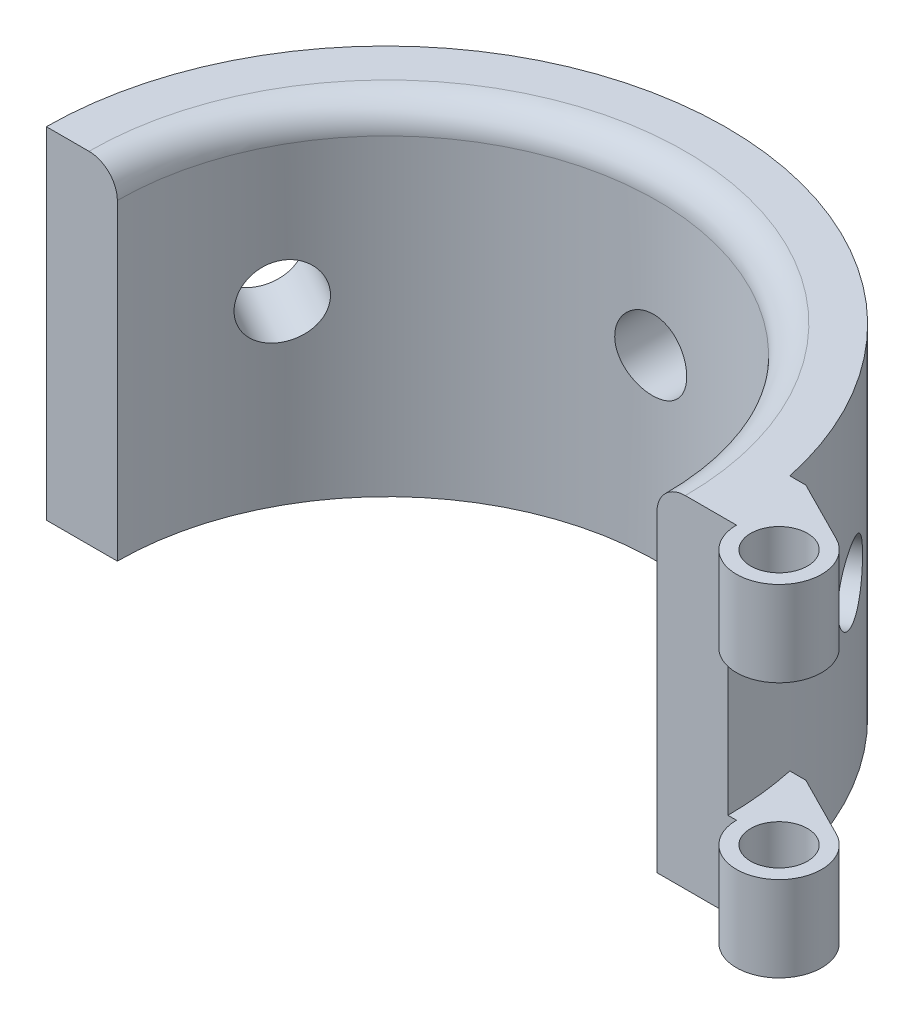
SolidWorks part; units mm, degrees
ref_plane "Front Plane" through (0, 0, 0) normal (0, 0, 1) x (1, 0, 0)
ref_plane "Top Plane" through (0, 0, 0) normal (0, 1, 0) x (1, 0, 0)
ref_plane "Right Plane" through (0, 0, 0) normal (1, 0, 0) x (0, 0, -1)
sketch "Sketch1" plane through (0, 0, 0) normal (0, 1, 0) x (1, 0, 0)
  line L1 (-78.9587, 0) -> (-17.9987, 0)
  arc A0 (-78.9587, 0) -> (-17.9987, 0) centre (-48.4787, -0.1303) cw
  dimension "D1" = 60.96
extrude "Boss-Extrude1" add sketch "Sketch1" along normal blind 30.48 contours L1 A0
ref_plane "Plane1" through (-17.9987, 30.48, 0) normal (1, 0, 0) x (0, 0, -1)
sketch "Sketch3" plane through (0, 0, 0) normal (0, 1, 0) x (1, 0, 0)
  line L0 (-78.9587, 0) -> (-17.9987, 0) construction
  circle A0 centre (-48.4787, 0) radius 24.13
  dimension "D1" = 48.26
extrude "Cut-Extrude4" cut sketch "Sketch3" along normal through all contours A0
sketch "Sketch4" plane through (0, 0, 0) normal (0, 0, 1) x (1, 0, 0)
  circle A0 centre (-48.8244, 15.7989) radius 3.175
  dimension "D1" = 6.35
extrude "Cut-Extrude5" cut sketch "Sketch4" against normal blind 63.754 contours A0
pattern_circular "CirPattern3" count 6 every 60 about axis through (-48.4787, 30.48, 0.1303) along (0, -1, 0) of "Cut-Extrude5"
sketch "Sketch5" plane through (0, 30.48, 0) normal (0, 1, 0) x (1, 0, 0)
  line L0 (-17.2367, 0) -> (-13.4267, 0)
  line L1 (-17.9987, 0) -> (-17.2367, 0)
  line L3 (-18.2527, 6.2015) -> (-17.2367, 6.2015)
  line L5 (-17.2367, 6.2015) -> (-11.7048, 3.3987)
  line L6 (-18.2527, 6.2015) -> (-18.6634, 6.2015)
  arc A0 (-17.2367, 0) -> (-11.7048, 3.3987) centre (-13.4267, 0) ccw
  circle A1 centre (-13.4267, 0) radius 2.54
  arc A2 (-17.9987, 0) -> (-78.9587, 0) centre (-48.4787, -0.1303) ccw construction
  dimension "D2" = 7.62
  dimension "D3" = 5.08
  dimension "D1" = 0.762
extrude "Boss-Extrude2" add sketch "Sketch5" against normal blind 7.62
pattern_linear "LPattern1" count 2 spacing 22.86 along (0, -1, 0) of "Boss-Extrude2"
fillet "Fillet1" radius 2.54 1 edges at (-48.4787, 30.48, -24.13)
